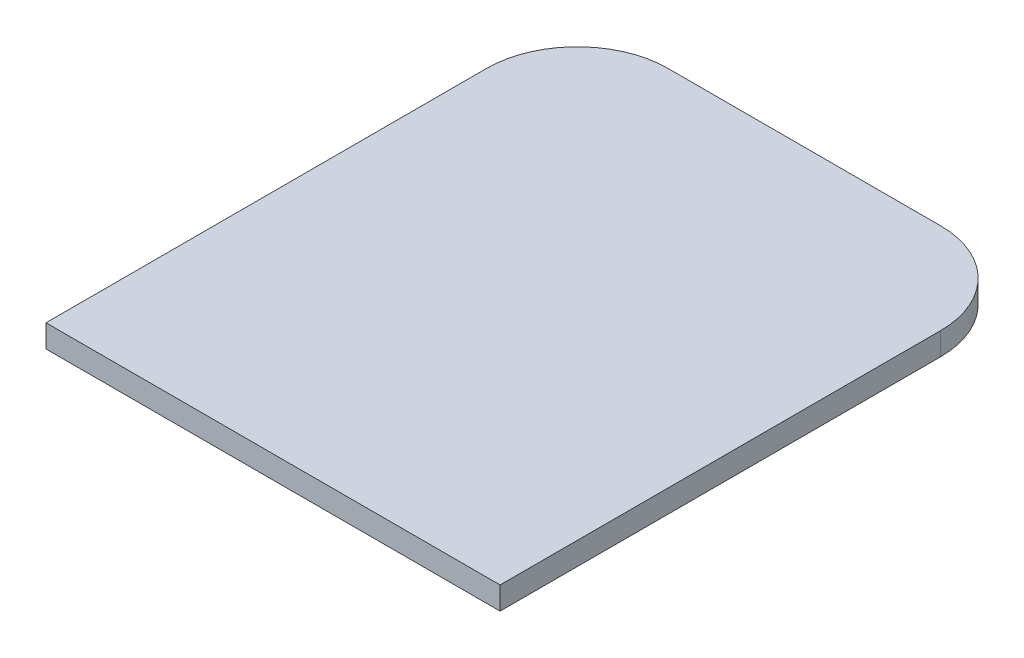
SolidWorks part; units mm, degrees
ref_plane "Front Plane" through (0, 0, 0) normal (0, 0, 1) x (1, 0, 0)
ref_plane "Top Plane" through (0, 0, 0) normal (0, 1, 0) x (1, 0, 0)
ref_plane "Right Plane" through (0, 0, 0) normal (1, 0, 0) x (0, 0, -1)
sketch "Sketch1" plane through (0, 0, 0) normal (0, 1, 0) x (1, 0, 0)
  line L1 (0, 0) -> (-20, 0)
  line L2 (0, 0) -> (0, 19.4)
  line L3 (-4, 23.4) -> (-16, 23.4)
  line L4 (-20, 0) -> (-20, 19.4)
  arc A0 (0, 19.4) -> (-4, 23.4) centre (-4, 19.4) ccw
  arc A1 (-20, 19.4) -> (-16, 23.4) centre (-16, 19.4) cw
  point P7 (0, 23.4)
  dimension "D3" = 4
  dimension "D1" = 20
  dimension "D2" = 23.4
extrude "Boss-Extrude1" add sketch "Sketch1" along normal blind 1
